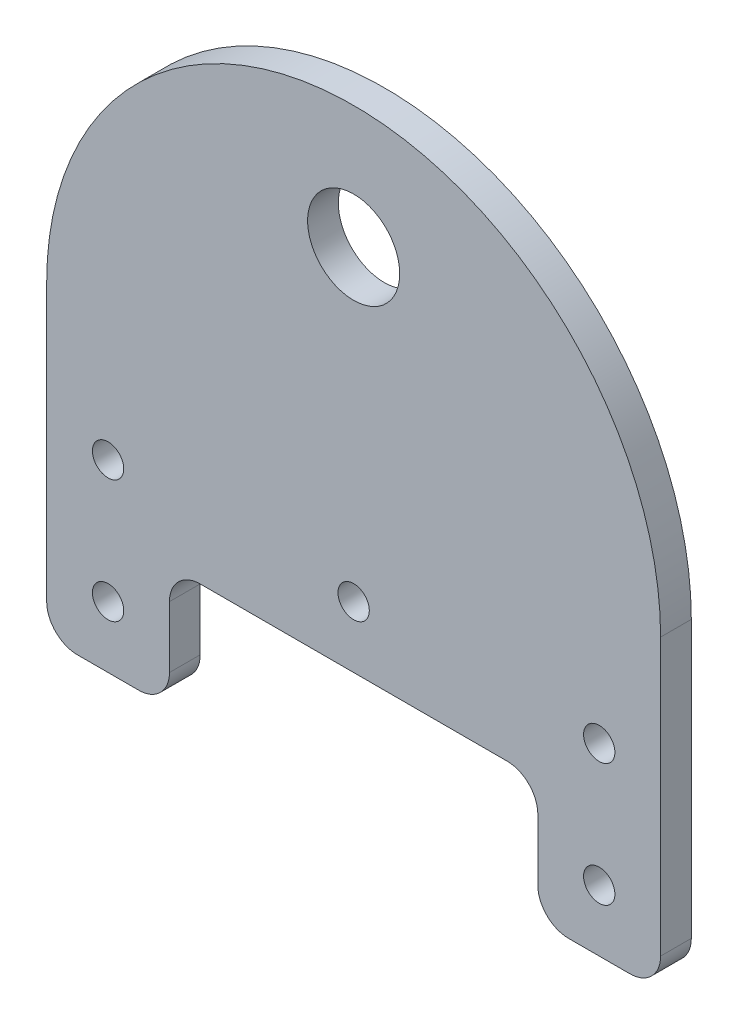
SolidWorks part; units mm, degrees
ref_plane "正面" through (0, 0, 0) normal (0, 0, 1) x (1, 0, 0)
ref_plane "平面" through (0, 0, 0) normal (0, 1, 0) x (1, 0, 0)
ref_plane "右側面" through (0, 0, 0) normal (1, 0, 0) x (0, 0, -1)
sketch "ｽｹｯﾁ1" plane through (0, 0, 0) normal (0, 0, 1) x (1, 0, 0)
  line L0 (-50, -60) -> (50, -60)
  line L1 (-50, -30) -> (-50, -60)
  line L2 (50, -30) -> (50, -60)
  line L3 (0, 0) -> (0, -30) construction
  line L4 (-40, -30) -> (-40, -50) construction
  line L5 (-40, -50) -> (40, -50) construction
  line L6 (40, -50) -> (40, -30) construction
  line L7 (-50, -30) -> (50, -30) construction
  circle A0 centre (0, 0) radius 7.5
  arc A2 (-50, -30) -> (50, -30) centre (0, -30) cw
  circle A3 centre (-40, -50) radius 2.55
  circle A4 centre (0, -50) radius 2.55
  circle A5 centre (40, -50) radius 2.55
  dimension "D1" = 100
  dimension "D2" = 15
  dimension "D3" = 30
  dimension "D4" = 30
  dimension "D8" = 5.1
  dimension "D5" = 10
  dimension "D6" = 10
  dimension "D7" = 10
extrude "ﾎﾞｽ - 押し出し1" add sketch "ｽｹｯﾁ1" along normal blind 5
sketch "ｽｹｯﾁ2" plane through (0, 0, 5) normal (0, 0, 1) x (1, 0, 0)
  line L0 (0, 0) -> (0, -89.872) construction
  line L1 (-50, -60) -> (-30, -60)
  line L2 (-50, -60) -> (-50, -80)
  line L3 (-50, -80) -> (-30, -80)
  line L4 (-30, -60) -> (-30, -80)
  line L5 (-40, -80) -> (-40, -60) construction
  line L6 (40, -80) -> (40, -60) construction
  line L7 (30, -60) -> (30, -80)
  line L8 (50, -80) -> (30, -80)
  line L9 (50, -60) -> (50, -80)
  line L10 (50, -60) -> (30, -60)
  circle A0 centre (-40, -70) radius 2.55
  circle A1 centre (-40, -50) radius 2.55 construction
  circle A2 centre (40, -70) radius 2.55
  dimension "D1" = 20
  dimension "D2" = 20
extrude "ﾎﾞｽ - 押し出し2" add sketch "ｽｹｯﾁ2" against normal up to surface (5 mm away) up to face at (-37.45, -50, 0)
fillet "ﾌｨﾚｯﾄ1" radius 5 6 edges at (-30, -60, 2.5) (30, -60, 2.5) (50, -80, 2.5) (30, -80, 2.5) (-30, -80, 2.5) (-50, -80, 2.5)
